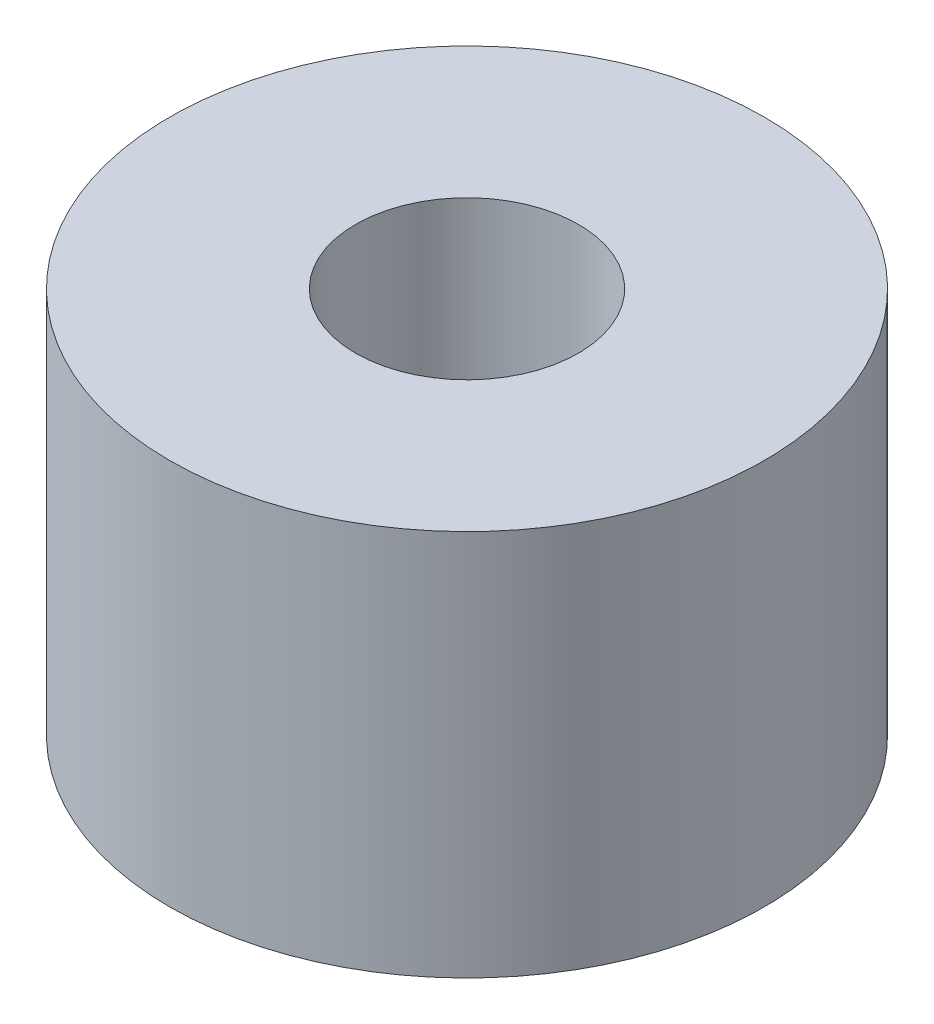
SolidWorks part; units mm, degrees
ref_plane "Front Plane" through (0, 0, 0) normal (0, 0, 1) x (1, 0, 0)
ref_plane "Top Plane" through (0, 0, 0) normal (0, 1, 0) x (1, 0, 0)
ref_plane "Right Plane" through (0, 0, 0) normal (1, 0, 0) x (0, 0, -1)
sketch "Sketch1" plane through (0, 0, 0) normal (0, 1, 0) x (1, 0, 0)
  circle A0 centre (0, 0) radius 100
  circle A1 centre (0, 0) radius 37.5
  dimension "D1" = 200
  dimension "D2" = 75
extrude "Boss-Extrude1" add sketch "Sketch1" along normal blind 130
